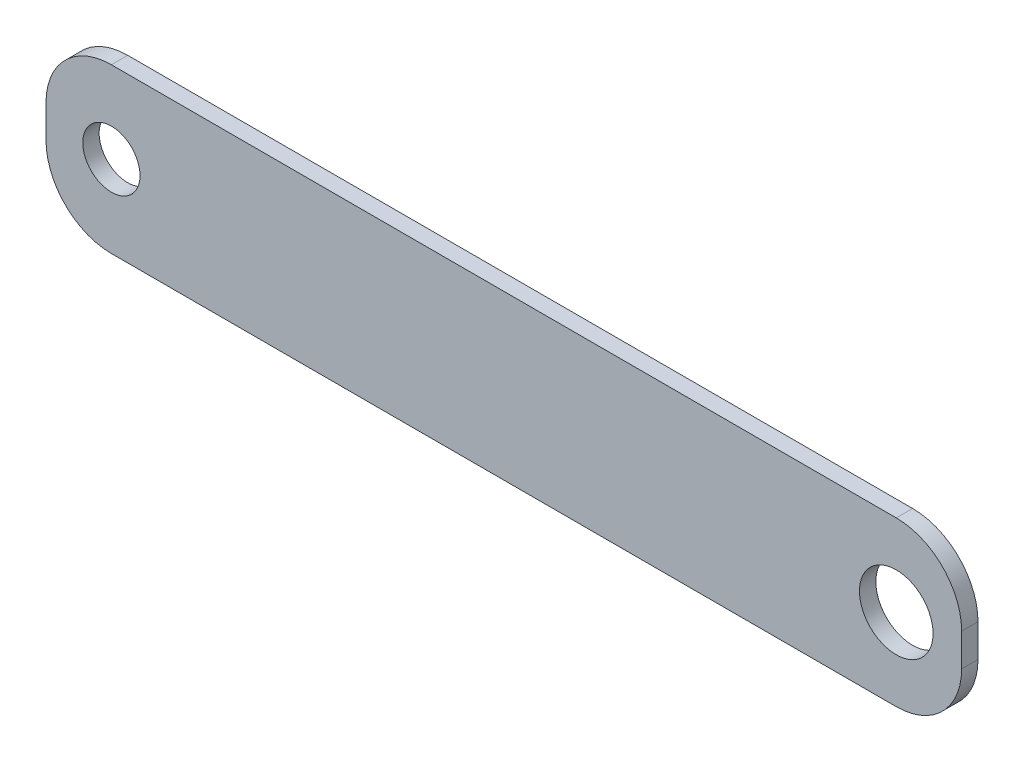
SolidWorks part; units mm, degrees
material "ABS PC"
ref_plane "Front Plane" through (0, 0, 0) normal (0, 0, 1) x (1, 0, 0)
ref_plane "Top Plane" through (0, 0, 0) normal (0, 1, 0) x (1, 0, 0)
ref_plane "Right Plane" through (0, 0, 0) normal (1, 0, 0) x (0, 0, -1)
sketch "Layout" plane through (0, 0, 0) normal (0, 0, 1) x (1, 0, 0)
  line L0 (-329.0442, 0) -> (309.3606, 0) construction
  line L1 (36.9648, 44.45) -> (341.7648, 44.45)
  line L2 (11.5648, 69.85) -> (11.5648, 82.55)
  line L3 (36.9648, 107.95) -> (211.9213, 107.95)
  line L4 (367.1648, 69.85) -> (367.1648, 82.55)
  line L5 (211.9213, 107.95) -> (324.9697, 107.95)
  line L8 (11.5648, 76.2) -> (367.1648, 76.2) construction
  line L14 (324.9697, 107.95) -> (341.7648, 107.95)
  circle A0 centre (36.9648, 76.2) radius 11.1125
  circle A1 centre (341.7648, 76.2) radius 14.2875
  circle A6 centre (341.7648, 76.2) radius 38.1 construction
  arc A8 (341.7648, 44.45) -> (367.1648, 69.85) centre (341.7648, 69.85) ccw
  arc A9 (341.7648, 107.95) -> (367.1648, 82.55) centre (341.7648, 82.55) cw
  arc A10 (36.9648, 44.45) -> (11.5648, 69.85) centre (36.9648, 69.85) cw
  arc A11 (11.5648, 82.55) -> (36.9648, 107.95) centre (36.9648, 82.55) cw
  point P12 (367.1648, 107.95)
  point P21 (11.5648, 107.95)
  dimension "D9" = 22.225
  dimension "D10" = 28.575
  dimension "D11" = 76.2
  dimension "D5" = 25.4
  dimension "D2" = 63.5
  dimension "D3" = 355.6
  dimension "D4" = 200.3564
  dimension "D8" = 25.4
  dimension "D14" = 25.4
extrude "Boss-Extrude1" add sketch "Layout" along normal blind 6.35
